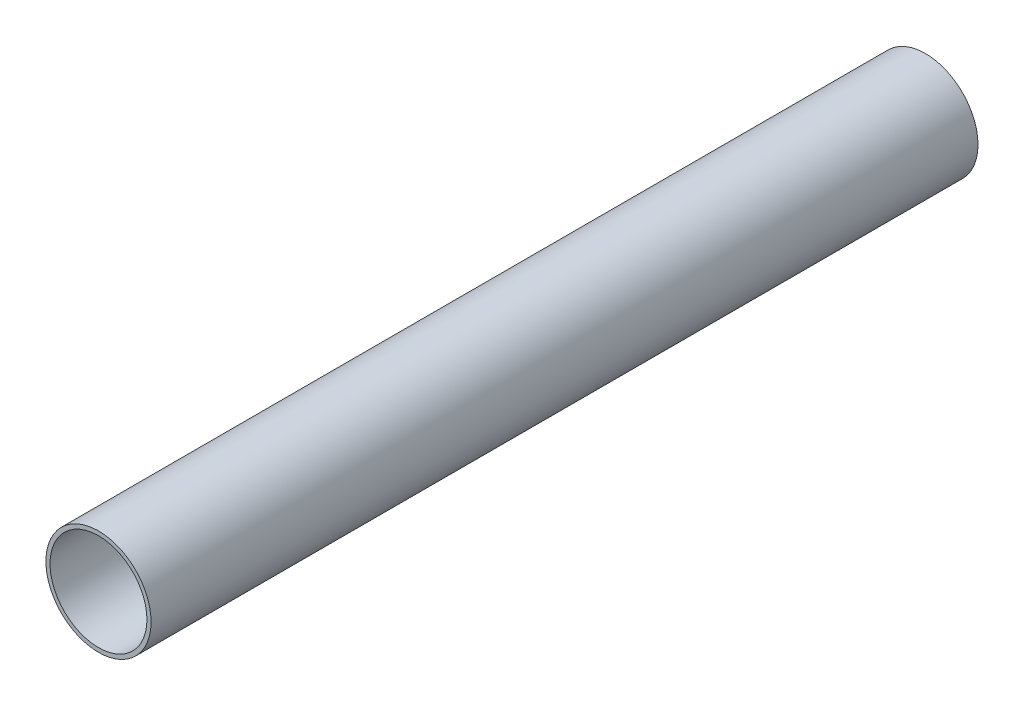
SolidWorks part; units mm, degrees
ref_plane "Front Plane" through (0, 0, 0) normal (0, 0, 1) x (1, 0, 0)
ref_plane "Top Plane" through (0, 0, 0) normal (0, 1, 0) x (1, 0, 0)
ref_plane "Right Plane" through (0, 0, 0) normal (1, 0, 0) x (0, 0, -1)
sketch "Sketch1" plane through (0, 0, 0) normal (0, 0, 1) x (1, 0, 0)
  circle A0 centre (0, 0) radius 15.9
  dimension "D1" = 31.8
extrude "Boss-Extrude1" add sketch "Sketch1" against normal blind 250
sketch "Sketch2" plane through (0, 0, 0) normal (0, 0, 1) x (1, 0, 0)
  circle A0 centre (0, 0) radius 14.65
  dimension "D1" = 29.3
extrude "Cut-Extrude1" cut sketch "Sketch2" against normal up to next
